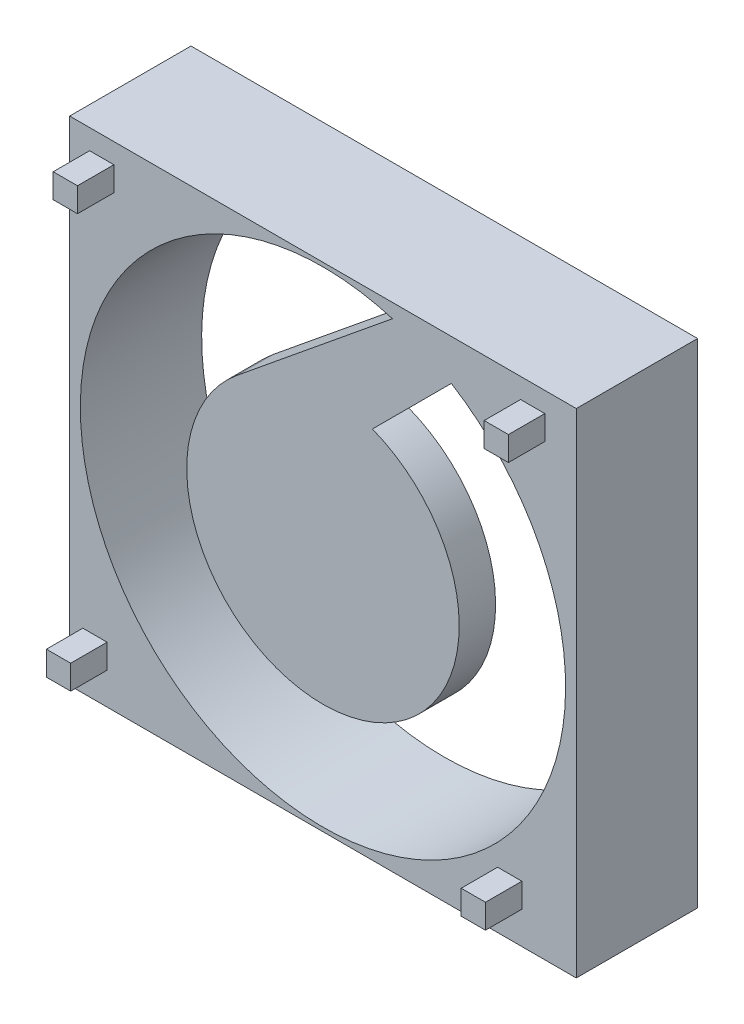
SolidWorks part; units mm, degrees
ref_plane "Front Plane" through (0, 0, 0) normal (0, 0, 1) x (1, 0, 0)
ref_plane "Top Plane" through (0, 0, 0) normal (0, 1, 0) x (1, 0, 0)
ref_plane "Right Plane" through (0, 0, 0) normal (1, 0, 0) x (0, 0, -1)
sketch "Sketch1" plane through (0, 0, 0) normal (0, 0, 1) x (1, 0, 0)
  line L1 (-20.88, -20.3264) -> (20.88, -20.3264)
  line L2 (-20.88, -20.3264) -> (-20.88, 20.3264)
  line L3 (-20.88, 20.3264) -> (20.88, 20.3264)
  line L4 (20.88, -20.3264) -> (20.88, 20.3264)
  line L5 (-20.88, -20.3264) -> (20.88, 20.3264) construction
  line L6 (-20.88, 20.3264) -> (20.88, -20.3264) construction
  circle A0 centre (0, 0) radius 20
  point P7 (-20.88, 20.3264)
  dimension "D1" = 40
extrude "Boss-Extrude1" add sketch "Sketch1" along normal blind 10
sketch "Sketch2" plane through (0, 0, 10) normal (0, 0, 1) x (1, 0, 0)
  line L0 (0, 0) -> (-7.0965, 8.7029) construction
  line L1 (-7.0965, 8.7029) -> (5.7298, 19.1617)
  line L2 (4.0755, 10.4638) -> (10.5825, 16.9709)
  arc A0 (-7.0965, 8.7029) -> (4.0755, 10.4638) centre (0, 0) ccw
  circle A1 centre (0, 0) radius 20 construction
  circle A3 centre (0, 0) radius 20
  arc A4 (10.5825, 16.9709) -> (5.7298, 19.1617) centre (0, 0) ccw
  dimension "D1" = 0
extrude "Boss-Extrude2" add sketch "Sketch2" against normal blind 3
sketch "Sketch3" plane through (0, 0, 10) normal (0, 0, 1) x (1, 0, 0)
  line L1 (18.2873, 18.6728) -> (16.2873, 18.6728)
  line L2 (18.2873, 18.6728) -> (18.2873, 16.6728)
  line L3 (18.2873, 16.6728) -> (16.2873, 16.6728)
  line L4 (16.2873, 18.6728) -> (16.2873, 16.6728)
  line L5 (-17.2364, 18.6728) -> (-19.2364, 18.6728)
  line L6 (-17.2364, 18.6728) -> (-17.2364, 16.6728)
  line L7 (-17.2364, 16.6728) -> (-19.2364, 16.6728)
  line L8 (-19.2364, 18.6728) -> (-19.2364, 16.6728)
  line L9 (-17.7969, -15.6917) -> (-19.7969, -15.6917)
  line L10 (-17.7969, -15.6917) -> (-17.7969, -17.6917)
  line L11 (-17.7969, -17.6917) -> (-19.7969, -17.6917)
  line L12 (-19.7969, -15.6917) -> (-19.7969, -17.6917)
  line L13 (16.3955, -15.6598) -> (14.3955, -15.6598)
  line L14 (16.3955, -15.6598) -> (16.3955, -17.6598)
  line L15 (16.3955, -17.6598) -> (14.3955, -17.6598)
  line L16 (14.3955, -15.6598) -> (14.3955, -17.6598)
  dimension "D1" = 2
  dimension "D2" = 2
  dimension "D3" = 2
  dimension "D4" = 2
  dimension "D5" = 2
  dimension "D6" = 2
  dimension "D7" = 2
  dimension "D8" = 2
  dimension "D9" = 2
  dimension "D10" = 2
extrude "Boss-Extrude3" add sketch "Sketch3" along normal blind 3 contours L13 L16 L15 L14 | L1 L4 L3 L2 | L10 L9 L12 L11 | L8 L7 L6 L5
